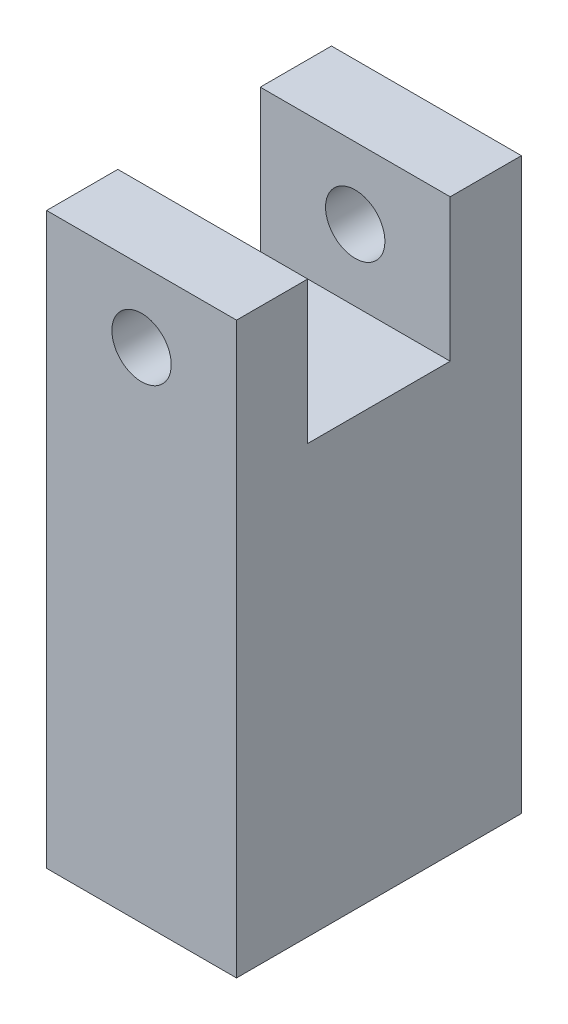
SolidWorks part; units mm, degrees
material "AISI 4340 Steel, annealed"
ref_plane "Front Plane" through (0, 0, 0) normal (0, 0, 1) x (1, 0, 0)
ref_plane "Top Plane" through (0, 0, 0) normal (0, 1, 0) x (1, 0, 0)
ref_plane "Right Plane" through (0, 0, 0) normal (1, 0, 0) x (0, 0, -1)
sketch "Sketch1" plane through (0, 0, 0) normal (0, 0, 1) x (1, 0, 0)
  line L1 (-12.7, 38.1) -> (12.7, 38.1)
  line L2 (-12.7, 38.1) -> (-12.7, -38.1)
  line L3 (-12.7, -38.1) -> (12.7, -38.1)
  line L4 (12.7, 38.1) -> (12.7, -38.1)
  line L5 (-12.7, 38.1) -> (12.7, -38.1) construction
  line L6 (-12.7, -38.1) -> (12.7, 38.1) construction
  point P0 (0, 0)
  dimension "D1" = 25.4
  dimension "D2" = 76.2
extrude "Boss-Extrude1" add sketch "Sketch1" along normal mid plane 38.1
sketch "Sketch2" plane through (12.7, 0, 0) normal (1, 0, 0) x (0, 0, -1)
  line L0 (-19.05, 38.1) -> (19.05, 38.1) construction
  line L1 (-9.525, 38.1) -> (9.525, 38.1)
  line L2 (-9.525, 38.1) -> (-9.525, 19.05)
  line L3 (-9.525, 19.05) -> (9.525, 19.05)
  line L4 (9.525, 38.1) -> (9.525, 19.05)
  line L5 (-9.525, 38.1) -> (9.525, 19.05) construction
  line L6 (-9.525, 19.05) -> (9.525, 38.1) construction
  line L7 (-9.525, 38.1) -> (-19.05, 38.1) construction
  line L8 (9.525, 38.1) -> (19.05, 38.1) construction
  point P0 (0, 28.575)
  line M8 (19.05, 38.1) -> (-19.05, 38.1)
  dimension "D1" = 19.05
extrude "Cut-Extrude1" cut sketch "Sketch2" against normal through all contours L4 L2 L3 M8
sketch "Sketch4" plane through (0, 0, 19.05) normal (0, 0, 1) x (1, 0, 0)
  line L0 (-12.7, 38.1) -> (-12.7, 19.05) construction
  line L1 (-12.7, 19.05) -> (12.7, 19.05) construction
  circle A0 centre (0, 28.575) radius 3.9688
  point P8 (-12.7, 28.575)
  point P9 (0, 19.05)
  dimension "D1" = 7.9375
extrude "Cut-Extrude2" cut sketch "Sketch4" against normal up to surface (38.1 mm away) up to face at (0, 0, -19.05)
